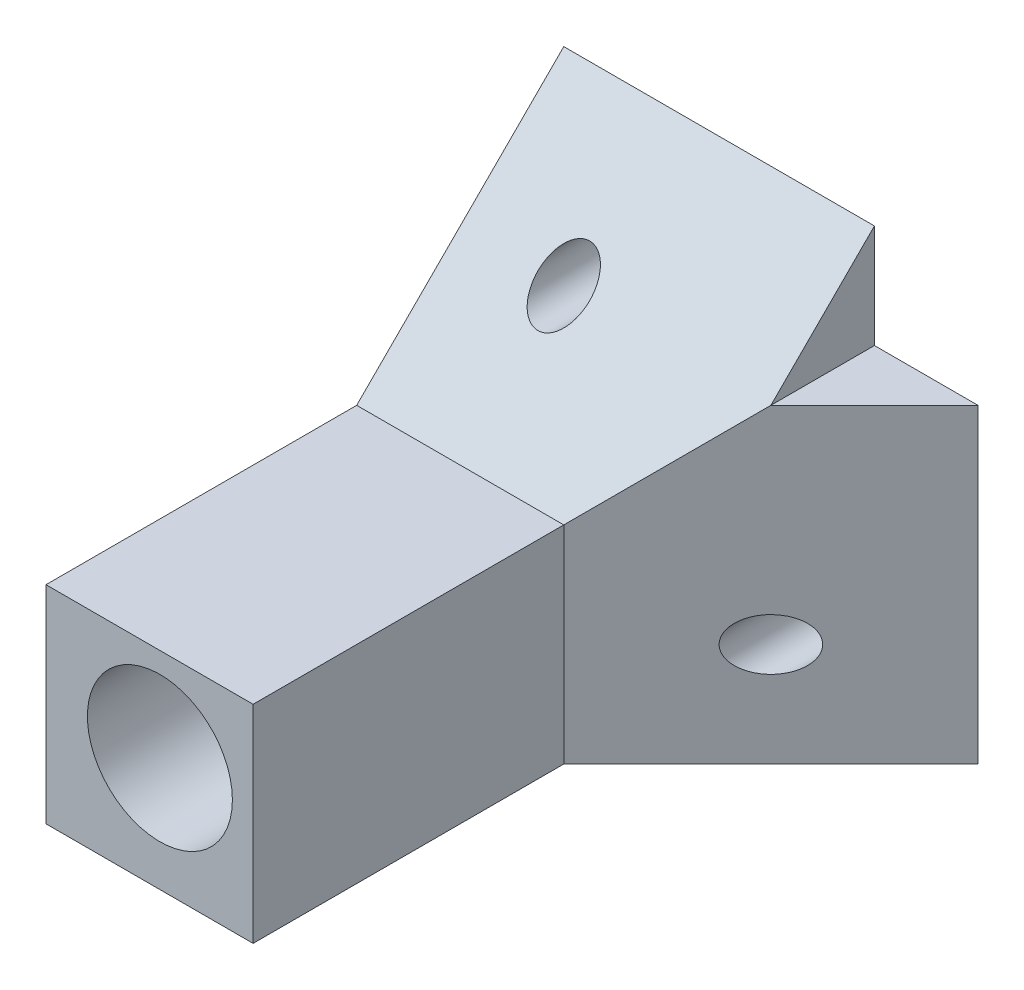
SolidWorks part; units mm, degrees
ref_plane "정면" through (0, 0, 0) normal (0, 0, 1) x (1, 0, 0)
ref_plane "윗면" through (0, 0, 0) normal (0, 1, 0) x (1, 0, 0)
ref_plane "우측면" through (0, 0, 0) normal (1, 0, 0) x (0, 0, -1)
sketch "스케치1" plane through (0, 0, 0) normal (0, 0, 1) x (1, 0, 0)
  line L1 (-10, 10) -> (10, 10)
  line L2 (-10, 10) -> (-10, -10)
  line L3 (-10, -10) -> (10, -10)
  line L4 (10, 10) -> (10, -10)
  line L5 (-10, 10) -> (10, -10) construction
  line L6 (-10, -10) -> (10, 10) construction
  point P0 (0, 0)
  dimension "D1" = 20
  dimension "D2" = 20
extrude "보스-돌출1" add sketch "스케치1" along normal blind 40
sketch "스케치2" plane through (10, 0, 0) normal (1, 0, 0) x (0, 0, -1)
  line L0 (0, -10) -> (0, 10) construction
  line L1 (-15, 7.5) -> (-5, 7.5)
  line L2 (-15, 7.5) -> (-15, -7.5)
  line L3 (-15, -7.5) -> (-5, -7.5)
  line L4 (-5, 7.5) -> (-5, -7.5)
  line L5 (-15, 7.5) -> (-5, -7.5) construction
  line L6 (-15, -7.5) -> (-5, 7.5) construction
  line L7 (-40, -10) -> (0, -10) construction
  point P0 (-10, 0)
  dimension "D1" = 10
  dimension "D2" = 10
  dimension "D3" = 15
  dimension "D4" = 10
extrude "컷-돌출1" cut sketch "스케치2" against normal blind 7.0711
sketch "스케치4" plane through (0, 0, 0) normal (0, 1, 0) x (1, 0, 0)
  line L0 (0, -30.773) -> (0, 0.8163) construction
pattern_circular "원형 패턴1" count 4 over 360 about axis through (0, 0, 0) along (0, 0, 1) of "컷-돌출1"
sketch "스케치5" plane through (0, 0, 40) normal (0, 0, 1) x (1, 0, 0)
  line L0 (-10, 10) -> (-10, -10) construction
  line L1 (-10, -10) -> (10, -10) construction
  line L2 (10, -10) -> (10, 10) construction
  line L3 (10, 10) -> (-10, 10) construction
  circle A0 centre (-5.5, 5.5) radius 3.5
  circle A1 centre (5.5, 5.5) radius 3.5
  circle A2 centre (-5.5, -5.5) radius 3.5
  circle A3 centre (5.5, -5.5) radius 3.5
  dimension "D1" = 7
  dimension "D2" = 7
  dimension "D3" = 7
  dimension "D4" = 7
  dimension "D5" = 4.5
  dimension "D6" = 4.5
  dimension "D7" = 4.5
  dimension "D8" = 4.5
  dimension "D9" = 4.5
  dimension "D10" = 4.5
  dimension "D11" = 4.5
  dimension "D12" = 4.5
extrude "컷-돌출2" cut sketch "스케치5" along a picked direction on the side against the normal blind 25
sketch "스케치6" plane through (0, 0, 0) normal (0, 0, -1) x (-1, 0, 0)
  line L5 (-14.8088, -2.95) -> (-14.8088, 2.95)
  line L7 (-14.8088, 2.95) -> (-2.95, 2.95)
  line L8 (-2.95, 2.95) -> (-2.95, 12.3603)
  line L10 (-2.95, 12.3603) -> (2.95, 12.3603)
  line L11 (2.95, 12.3603) -> (2.95, 2.95)
  line L12 (2.95, 2.95) -> (13.8521, 2.95)
  line L14 (13.8521, 2.95) -> (13.8521, -2.95)
  line L15 (13.8521, -2.95) -> (2.95, -2.95)
  line L16 (2.95, -2.95) -> (2.95, -13.9757)
  line L18 (2.95, -13.9757) -> (-2.95, -13.9757)
  line L19 (-2.95, -13.9757) -> (-2.95, -2.95)
  line L20 (-2.95, -2.95) -> (-14.8088, -2.95)
  dimension "D1" = 5.9
  dimension "D2" = 2.95
  dimension "D3" = 5.9
  dimension "D4" = 5.9
  dimension "D5" = 5.9
  dimension "D6" = 2.95
  dimension "D7" = 2.95
  dimension "D8" = 2.95
extrude "컷-돌출3" cut sketch "스케치6" against normal blind 5
sketch "스케치8" plane through (0, 0, 0) normal (0, 1, 0) x (1, 0, 0)
  line L5 (-11.0684, 1.3381) -> (11.5394, 1.3381)
  line L6 (-11.0684, 1.3381) -> (-11.0684, -40.7573)
  line L7 (-11.0684, -40.7573) -> (11.5394, -40.7573)
  line L8 (11.5394, 1.3381) -> (11.5394, -40.7573)
sketch "스케치9" plane through (0, 0, 5) normal (0, 0, -1) x (-1, 0, 0)
  line L1 (-2.9289, 2.9289) -> (2.95, 2.9289)
  line L2 (-2.9289, 2.9289) -> (-2.9289, -2.95)
  line L3 (-2.9289, -2.95) -> (2.95, -2.95)
  line L4 (2.95, 2.9289) -> (2.95, -2.95)
extrude "컷-돌출5" cut sketch "스케치9" against normal blind 5
sketch "스케치11" plane through (10, 0, 0) normal (1, 0, 0) x (0, 0, -1)
  line L1 (-15, 15) -> (-25, 15)
  line L2 (-15, 15) -> (-15, -15)
  line L3 (-15, -15) -> (-25, -15)
  line L4 (-25, 15) -> (-25, -15)
  dimension "D1" = 30
  dimension "D2" = 10
  dimension "D3" = 15
extrude "보스-돌출2" add sketch "스케치11" along normal blind 10
sketch "스케치12" plane through (0, 15, 0) normal (0, 1, 0) x (1, 0, 0)
  line L0 (20, -15) -> (10, -25)
  line L1 (10, -25) -> (20, -25)
  line L2 (20, -25) -> (20, -15)
extrude "컷-돌출6" cut sketch "스케치12" against normal blind 30
sketch "스케치14" plane through (0, 0, 0) normal (1, 0, 0) x (0, 0, -1)
  line L0 (-45.6435, 0) -> (9.8052, 0) construction
sketch "스케치13" plane through (0, 0, 15) normal (0, 0, -1) x (-1, 0, 0)
  line L0 (-10, 2.95) -> (-10, 10) construction
  line L1 (-10, -10) -> (-10, -2.95) construction
  line L4 (-20, -15) -> (-10, -15) construction
  line L5 (-20, 15) -> (-10, 15) construction
  circle A0 centre (-15, -5) radius 1.25
  circle A1 centre (-15, 5) radius 1.25
  dimension "D5" = 2.5
  dimension "D6" = 2.5
  dimension "D1" = 5
  dimension "D2" = 5
  dimension "D3" = 10
  dimension "D4" = 10
extrude "컷-돌출7" cut sketch "스케치13" against normal blind 10
pattern_circular "원형 패턴2" count 4 over 360 about axis through (0, 0, 0) along (0, 0, 1) of "컷-돌출7", "컷-돌출6", "보스-돌출2"
ref_plane "평면1" through (0, 0, 25) normal (0, 0, -1) x (-1, 0, 0)
sketch "스케치16" plane through (0, -10, 0) normal (0, -1, 0) x (1, 0, 0)
  line L0 (-2.9289, 10) -> (2.9289, 10) construction
  line L1 (10, 0) -> (-10, 0)
  line L2 (10, 0) -> (10, 10)
  line L3 (10, 10) -> (-10, 10)
  line L4 (-10, 0) -> (-10, 10)
  dimension "D1" = 0
extrude "컷-돌출11" cut sketch "스케치16" against normal blind 40
sketch "스케치17" plane through (0, 0, 10) normal (0, 0, -1) x (-1, 0, 0)
  line L1 (-10, 10) -> (10, 10)
  line L2 (-10, 10) -> (-10, -10)
  line L3 (-10, -10) -> (10, -10)
  line L4 (10, 10) -> (10, -10)
  line L5 (-10, 10) -> (10, -10) construction
  line L6 (-10, -10) -> (10, 10) construction
  line L7 (-2.9289, 2.9289) -> (2.9289, 2.9289)
  line L8 (-2.9289, 2.9289) -> (-2.9289, -2.9289)
  line L9 (-2.9289, -2.9289) -> (2.9289, -2.9289)
  line L10 (2.9289, 2.9289) -> (2.9289, -2.9289)
  line L11 (-2.9289, 2.9289) -> (2.9289, -2.9289) construction
  line L12 (-2.9289, -2.9289) -> (2.9289, 2.9289) construction
  point P0 (0, 0)
  point P7 (0, 0)
extrude "컷-돌출12" cut sketch "스케치17" against normal blind 5
sketch "스케치18" plane through (0, 10, 0) normal (0, -1, 0) x (1, 0, 0)
  line L0 (10, 25) -> (15, 25)
  line L1 (15, 25) -> (15, 20)
  line L2 (15, 20) -> (10, 25)
extrude "컷-돌출13" cut sketch "스케치18" against normal blind 10 and the other way through all
sketch "스케치19" plane through (0, 0, 0) normal (0, 1, 0) x (1, 0, 0)
  line L1 (-31.1319, 8.0592) -> (50.4041, 8.0592)
  line L2 (-31.1319, 8.0592) -> (-31.1319, -60.7276)
  line L3 (-31.1319, -60.7276) -> (50.4041, -60.7276)
  line L4 (50.4041, 8.0592) -> (50.4041, -60.7276)
extrude "컷-돌출16" cut sketch "스케치19" against normal blind 400 contours L1 L4 L3 L2
sketch "스케치20" plane through (0, 0, 0) normal (1, 0, 0) x (0, 0, -1)
  line L1 (-53.3755, 28.6467) -> (19.7058, 28.6467)
  line L2 (-53.3755, 28.6467) -> (-53.3755, -15.7116)
  line L3 (-53.3755, -15.7116) -> (19.7058, -15.7116)
  line L4 (19.7058, 28.6467) -> (19.7058, -15.7116)
extrude "컷-돌출18" cut sketch "스케치20" against normal blind 400
sketch "스케치21" plane through (0, 0, 15) normal (0, 0, -1) x (-1, 0, 0)
  circle A0 centre (-15, 5) radius 1.25
